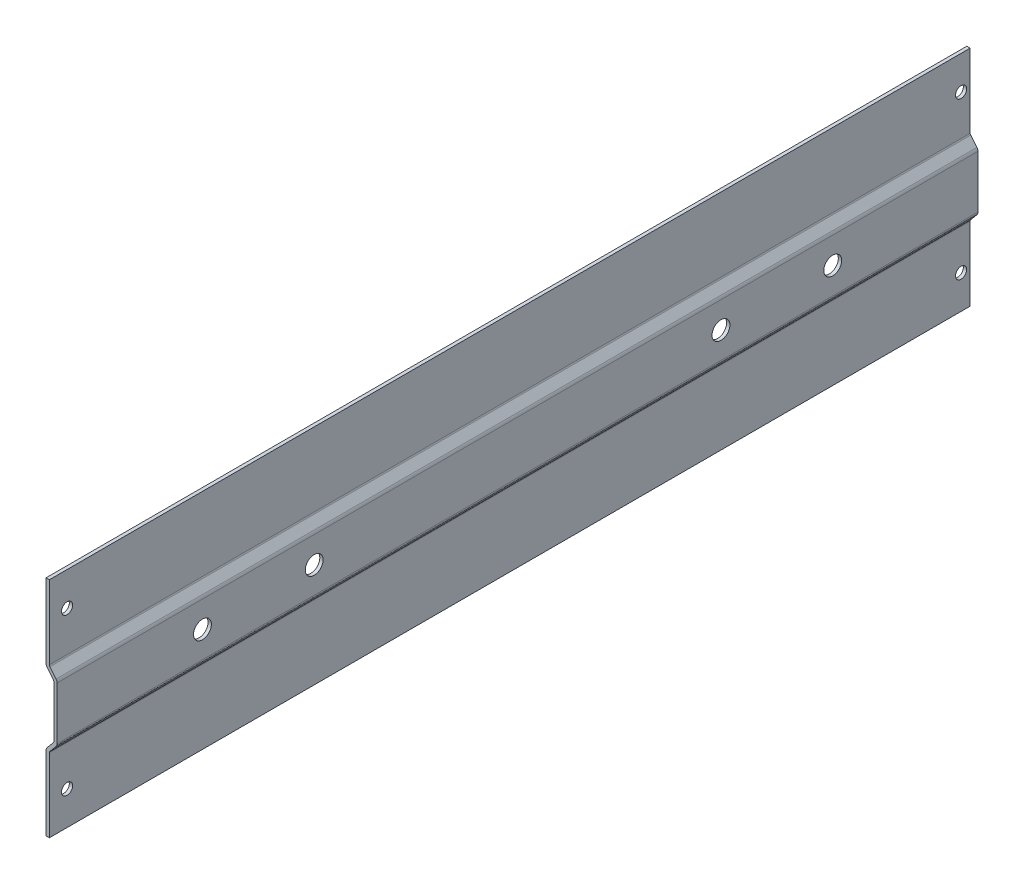
SolidWorks part; units mm, degrees
material "Q235"
ref_plane "前视基准面" through (0, 0, 0) normal (0, 0, 1) x (1, 0, 0)
ref_plane "上视基准面" through (0, 0, 0) normal (0, 1, 0) x (1, 0, 0)
ref_plane "右视基准面" through (0, 0, 0) normal (1, 0, 0) x (0, 0, -1)
sketch "草图1" plane through (0, 0, 0) normal (0, 0, 1) x (1, 0, 0)
  line L0 (0, 0) -> (0, 67.7496)
  line L1 (0, 67.7496) -> (7, 76.0919)
  line L2 (7, 76.0919) -> (7, 123.9081)
  line L3 (7, 123.9081) -> (0, 132.2504)
  line L4 (0, 132.2504) -> (0, 200)
  line L5 (0, 200) -> (3, 200)
  line L6 (3, 200) -> (3, 133.3423)
  line L7 (3, 133.3423) -> (10, 125)
  line L8 (10, 125) -> (10, 75)
  line L9 (10, 75) -> (3, 66.6577)
  line L10 (3, 66.6577) -> (3, 0)
  line L11 (3, 0) -> (0, 0)
  line L12 (10, 100) -> (-38.6032, 100) construction
  point P12 (-14.3016, 100)
  point P14 (3.5, 128.0792)
  dimension "D1" = 3
  dimension "D2" = 3
  dimension "D3" = 200
  dimension "D4" = 50
  dimension "D5" = 220
  dimension "D6" = 3
  dimension "D7" = 220
  dimension "D8" = 3
  dimension "D9" = 10
  dimension "D10" = 100
extrude "凸台-拉伸1" add sketch "草图1" along normal blind 824
fillet "圆角1" radius 4 4 edges at (0, 67.7496, 412) (0, 132.2504, 412) (10, 75, 412) (10, 125, 412)
fillet "圆角2" radius 2 4 edges at (7, 76.0919, 412) (7, 123.9081, 412) (3, 66.6577, 412) (3, 133.3423, 412)
hole_wizard "Ø16.0 (16) 直径孔1" positions "草图2" profile "草图3" hole size "Ø16.0" standard "GB"
sketch "草图2" plane through (10, 0, 0) normal (1, 0, 0) x (0, 0, -1)
  line L3 (-824, 200) -> (0, 200) construction
  line L4 (0, 76.4559) -> (0, 123.5441) construction
  line L5 (-824, 76.4559) -> (-824, 123.5441) construction
  point P0 (-694, 100)
  point P2 (-130, 100)
  point P19 (-594, 100)
  point P21 (-230, 100)
  dimension "D1" = 100
  dimension "D2" = 130
  dimension "D3" = 100
  dimension "D4" = 130
  dimension "D5" = 100
sketch "草图3" plane through (10, 100, 694) normal (0, 1, 0) x (0, 0, -1)
  line L0 (0, 0) -> (0, 29.3069)
  line L1 (0, 29.3069) -> (8, 24.5)
  line L2 (8, 24.5) -> (8, 0)
  line L5 (8, 0) -> (0, 0)
  line L10 (0, 29.3069) -> (-8, 24.5) construction
  line L11 (0, -6.35) -> (0, 107.95) construction
  dimension "孔直径" = 16
  dimension "孔深度" = 24.5
  dimension "导头角度" = 118
hole_wizard "Ø10.0 (10) 直径孔1" positions "草图4" profile "草图5" hole size "Ø10.0" standard "GB" end condition through all
sketch "草图4" plane through (0, 0, 0) normal (-1, 0, 0) x (0, 0, 1)
  line L0 (0, 200) -> (0, 133.7062) construction
  line L4 (824, 200) -> (0, 200) construction
  point P0 (8.14, 170)
  point P2 (8.14, 30)
  point P4 (808.14, 170)
  point P6 (808.14, 30)
  dimension "D1" = 800
  dimension "D2" = 8.14
  dimension "D3" = 30
  dimension "D4" = 140
sketch "草图5" plane through (0, 170, 8.14) normal (0, 1, 0) x (0, 0, 1)
  line L0 (0, 0) -> (0, 10)
  line L1 (0, 10) -> (5, 10)
  line L2 (5, 10) -> (5, 0)
  line L5 (5, 0) -> (0, 0)
  line L11 (0, -6.35) -> (0, 107.95) construction
  dimension "通孔孔直径" = 10
  dimension "通孔孔深度" = 10
